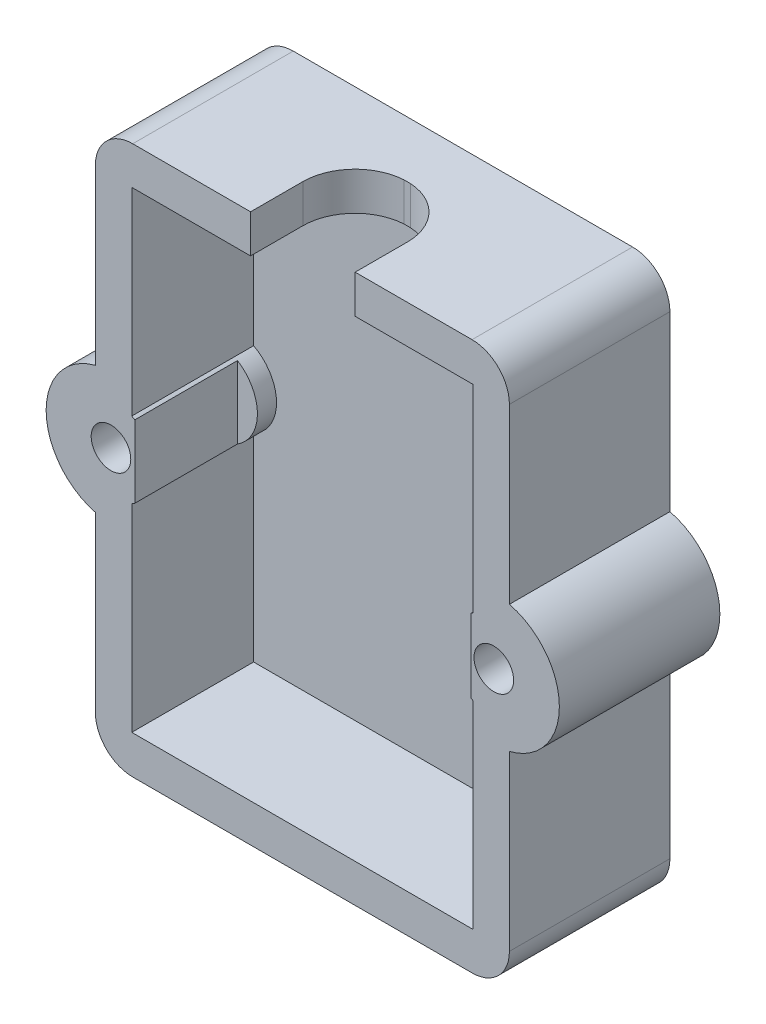
SolidWorks part; units mm, degrees
ref_plane "Front Plane" through (0, 0, 0) normal (0, 0, 1) x (1, 0, 0)
ref_plane "Top Plane" through (0, 0, 0) normal (0, 1, 0) x (1, 0, 0)
ref_plane "Right Plane" through (0, 0, 0) normal (1, 0, 0) x (0, 0, -1)
sketch "Sketch1" plane through (0, 0, 0) normal (0, 0, 1) x (1, 0, 0)
  line L0 (0, 0) -> (0, 25.5) construction
  line L1 (-15, 25.5) -> (15, 25.5) construction
  line L2 (-10.225, 13.5) -> (0, 13.5) construction
  line L3 (0, 13.5) -> (10.225, 13.5) construction
  line L4 (-11.11, 0.8164) -> (-11.11, 10.0908)
  line L9 (0, 25.1336) -> (0, -0.2336) construction
  line L10 (-9.06, 13.5) -> (9.06, 13.5) construction
  line L11 (-9.11, 28.1836) -> (9.06, 28.1836)
  line L12 (11.06, 0.8164) -> (11.06, 10.0908)
  line L13 (-9.11, -1.1836) -> (9.06, -1.1836)
  line L18 (-11.11, 16.9092) -> (-11.11, 26.1836)
  line L20 (11.06, 16.9092) -> (11.06, 26.1836)
  arc A2 (11.06, 16.9092) -> (11.06, 10.0908) centre (10.225, 13.5) cw
  arc A3 (-11.11, 16.9092) -> (-11.11, 10.0908) centre (-10.225, 13.5) ccw
  arc A4 (-11.11, 0.8164) -> (-9.11, -1.1836) centre (-9.11, 0.8164) ccw
  arc A5 (11.06, 0.8164) -> (9.06, -1.1836) centre (9.06, 0.8164) cw
  arc A6 (9.06, 28.1836) -> (11.06, 26.1836) centre (9.06, 26.1836) cw
  arc A8 (-11.11, 26.1836) -> (-9.11, 28.1836) centre (-9.11, 26.1836) cw
  point P11 (-13.7472, 13.5)
  point P33 (13.735, 13.5)
  dimension "D1" = 2
  dimension "D2" = 6.8185
  dimension "D3" = 29.3672
  dimension "D4" = 3.51
extrude "Boss-Extrude2" add sketch "Sketch1" along normal blind 8.595 contours L11 A6 L20 A2 L12 A5 L13 A4 L4 A3 L18 A8
sketch "Sketch2" plane through (0, 0, 8.595) normal (0, 0, 1) x (1, 0, 0)
  line L6 (-0.025, -1.1836) -> (-0.025, 28.1836) construction
  line L7 (-9.11, -1.1836) -> (9.06, -1.1836) construction
  line L8 (-9.11, 28.1836) -> (9.06, 28.1836) construction
  line L9 (13.735, 13.5) -> (-13.7472, 13.5) construction
  line L10 (-0.025, -0.2133) -> (-0.025, 25.2203) construction
  line L11 (-10.5637, 13.5) -> (9.8863, 13.5) construction
  line L12 (-9.1625, 15.5286) -> (-9.1625, 26.1364)
  line L13 (-9.1625, 0.8614) -> (9.1125, 0.8614)
  line L14 (-9.1625, 0.8614) -> (-9.1625, 11.4714)
  line L15 (-9.1625, 26.1364) -> (9.1125, 26.1364)
  line L16 (9.1125, 0.8614) -> (9.1125, 11.4714)
  line L17 (-0.025, 26.1364) -> (-0.025, 0.8614) construction
  line L18 (-9.075, 13.5) -> (9.075, 13.5) construction
  line L19 (9.1125, 15.5286) -> (9.1125, 26.1364)
  line L21 (-9.11, -1.1836) -> (9.06, -1.1836) construction
  arc A2 (11.06, 10.0908) -> (11.06, 16.9092) centre (10.225, 13.5) ccw construction
  arc A3 (-11.11, 16.9092) -> (-11.11, 10.0908) centre (-10.225, 13.5) ccw construction
  arc A4 (-9.1625, 11.4714) -> (-9.1625, 15.5286) centre (-10.225, 13.5) ccw
  arc A5 (9.1125, 11.4714) -> (9.1125, 15.5286) centre (10.175, 13.5) cw
  point P6 (-0.025, 13.5)
  dimension "D1" = 25.275
  dimension "D2" = 18.275
  dimension "D4" = 2.045
sketch "Sketch5" plane through (0, 0, 8.595) normal (0, 0, 1) x (1, 0, 0)
  line L0 (-0.025, 28.1836) -> (-0.025, -1.1836) construction
  line L1 (-11.11, 0.8164) -> (-11.11, 10.0908) construction
  line L2 (-9.11, -1.1836) -> (9.06, -1.1836) construction
  circle A0 centre (-10.275, 13.5) radius 1.06
  circle A1 centre (10.225, 13.5) radius 1.06
  dimension "D1" = 20.17
  dimension "D3" = 2.12
  dimension "D2" = 11.2744
  dimension "D4" = 0.835
  dimension "D5" = 14.6836
extrude "Cut-Extrude3" cut sketch "Sketch5" against normal up to next
extrude "Cut-Extrude4" cut sketch "Sketch2" against normal blind 6.525
sketch "Sketch3" plane through (0, 28.1836, 0) normal (0, 1, 0) x (1, 0, 0)
  line L0 (0, 0) -> (0, -8.595) construction
  line L2 (11.06, -4.2975) -> (-11.11, -4.2975) construction
  line L7 (-0.1673, -3.005) -> (0.1673, -3.005)
  line L8 (-2.8, -5.8) -> (-2.8, -8.595)
  line L9 (-2.8, -8.595) -> (2.8, -8.595)
  line L10 (2.8, -5.8) -> (2.8, -8.595)
  line L11 (0, -8.595) -> (0, -3.005) construction
  line L12 (-2.8, -5.8) -> (2.8, -5.8) construction
  line L16 (-9.11, -8.595) -> (-9.11, 0) construction
  line L17 (-9.11, 0) -> (9.06, 0) construction
  arc A0 (2.8, -5.8) -> (-2.8, -5.8) centre (0, -5.8) ccw
  arc A1 (-0.1673, -8.595) -> (0.1673, -8.595) centre (0, -5.8) ccw
  line M4 (-9.11, -8.595) -> (9.06, -8.595)
  dimension "D1" = 8.9427
  dimension "D2" = 5.6
  dimension "D3" = 5.59
  dimension "D4" = 3.005
  dimension "D5" = 4.2975
extrude "Cut-Extrude2" cut sketch "Sketch3" against normal up to next contours L10 A0 L7 L8 L9 M4
sketch "Sketch7" plane through (0, 0, 8.595) normal (0, 0, 1) x (1, 0, 0)
  line L0 (-9, 1.2233) -> (9, 1.2233)
  line L1 (-9, 1.2233) -> (-9, 25.8733)
  line L2 (-9, 25.8733) -> (9, 25.8733)
  line L3 (9, 1.2233) -> (9, 25.8733)
  line L6 (-9.1625, 0.8614) -> (9.1125, 0.8614) construction
  point P4 (0, 1.2233)
  dimension "D1" = 18
  dimension "D2" = 0.3619
  dimension "D3" = 25.0119
extrude "Cut-Extrude6" cut sketch "Sketch7" against normal blind 5.5
